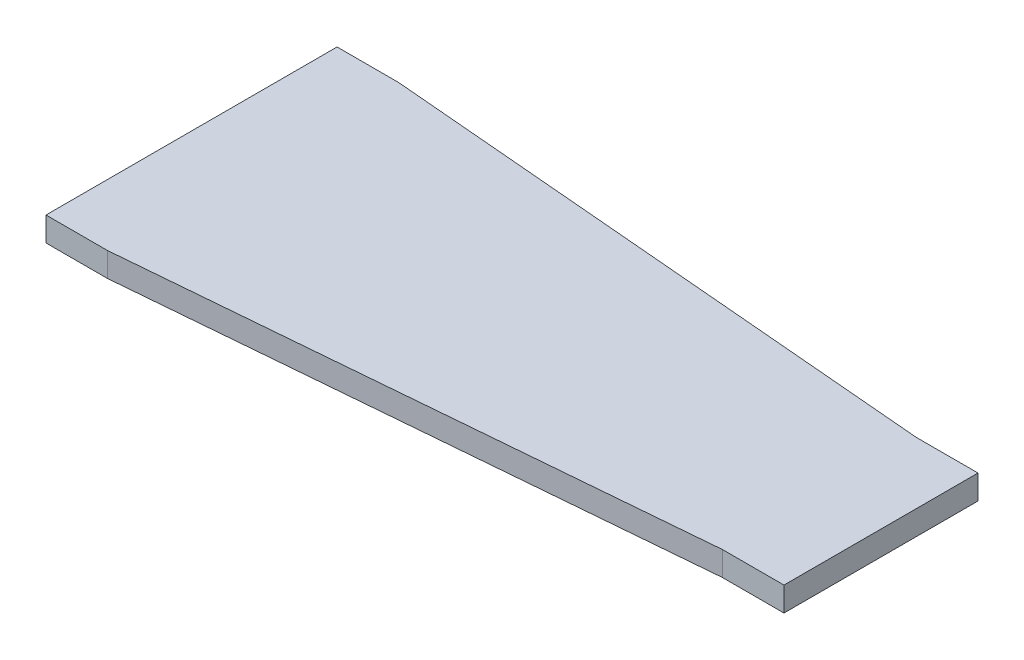
SolidWorks part; units mm, degrees
ref_plane "Front Plane" through (0, 0, 0) normal (0, 0, 1) x (1, 0, 0)
ref_plane "Top Plane" through (0, 0, 0) normal (0, 1, 0) x (1, 0, 0)
ref_plane "Right Plane" through (0, 0, 0) normal (1, 0, 0) x (0, 0, -1)
sketch "Sketch1" plane through (0, 0, 0) normal (0, 1, 0) x (1, 0, 0)
  line L1 (233.45, 40) -> (258.85, 40)
  line L3 (233.45, -40) -> (258.85, -40)
  line L4 (258.85, 40) -> (258.85, -40)
  line L5 (0, 60) -> (-25.4, 60)
  line L7 (0, -60) -> (-25.4, -60)
  line L8 (-25.4, 60) -> (-25.4, -60)
  spline S0 degree 1 poles (0, 60) (233.45, 40) knots 0 0 1 1 construction
  spline S1 degree 1 poles (0, 60) (233.45, 40) knots 0 0 1 1
  spline S2 degree 1 poles (0, -60) (233.45, -40) knots 0 0 1 1 construction
  spline S3 degree 1 poles (0, -60) (233.45, -40) knots 0 0 1 1
  dimension "D1" = 25.4
  dimension "D2" = 25.4
extrude "Boss-Extrude1" add sketch "Sketch1" along normal blind 10
